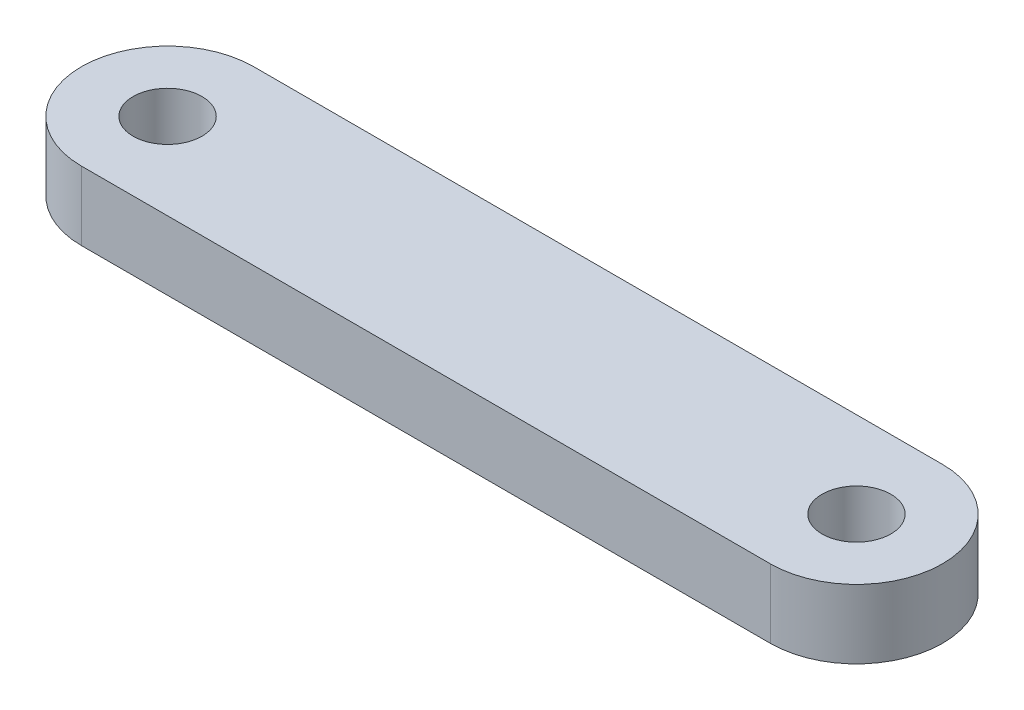
SolidWorks part; units mm, degrees
ref_plane "Front Plane" through (0, 0, 0) normal (0, 0, 1) x (1, 0, 0)
ref_plane "Top Plane" through (0, 0, 0) normal (0, 1, 0) x (1, 0, 0)
ref_plane "Right Plane" through (0, 0, 0) normal (1, 0, 0) x (0, 0, -1)
sketch "Sketch1" plane through (0, 0, 0) normal (0, 1, 0) x (1, 0, 0)
  line L0 (0, 0) -> (20, 0) construction
  line L1 (0, 2.5) -> (20, 2.5)
  line L2 (0, -2.5) -> (20, -2.5)
  arc A0 (0, 2.5) -> (0, -2.5) centre (0, 0) ccw
  arc A1 (20, -2.5) -> (20, 2.5) centre (20, 0) ccw
  circle A2 centre (0, 0) radius 1
  circle A3 centre (20, 0) radius 1
  point P3 (10, 0)
  dimension "D2" = 2.5
  dimension "D4" = 2
  dimension "D5" = 2
  dimension "D1" = 20
extrude "Boss-Extrude1" add sketch "Sketch1" along normal blind 2
